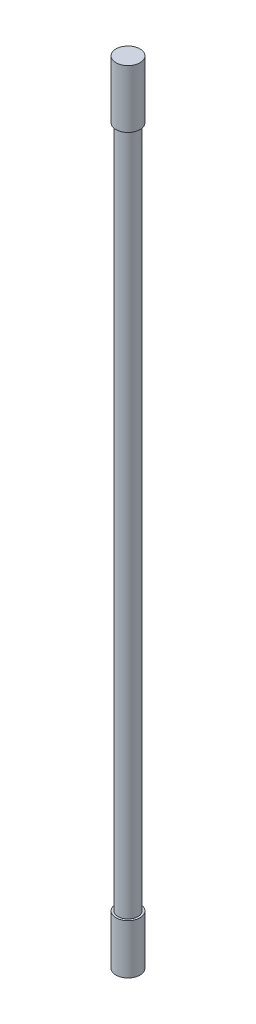
SolidWorks part; units mm, degrees
ref_plane "Front Plane" through (0, 0, 0) normal (0, 0, 1) x (1, 0, 0)
ref_plane "Top Plane" through (0, 0, 0) normal (0, 1, 0) x (1, 0, 0)
ref_plane "Right Plane" through (0, 0, 0) normal (1, 0, 0) x (0, 0, -1)
sketch "Sketch1" plane through (0, 0, 0) normal (0, 1, 0) x (1, 0, 0)
  circle A0 centre (0, 0) radius 2.9
  dimension "D1" = 5.8
extrude "Boss-Extrude1" add sketch "Sketch1" along normal blind 12
sketch "Sketch2" plane through (0, 12, 0) normal (0, 1, 0) x (1, 0, 0)
  circle A0 centre (0, 0) radius 2.4
  dimension "D1" = 4.8
extrude "Boss-Extrude2" add sketch "Sketch2" along normal blind 165
sketch "Sketch3" plane through (0, 177, 0) normal (0, 1, 0) x (1, 0, 0)
  circle A0 centre (0, 0) radius 2.9
  dimension "D1" = 5.8
extrude "Boss-Extrude3" add sketch "Sketch3" along normal blind 14
